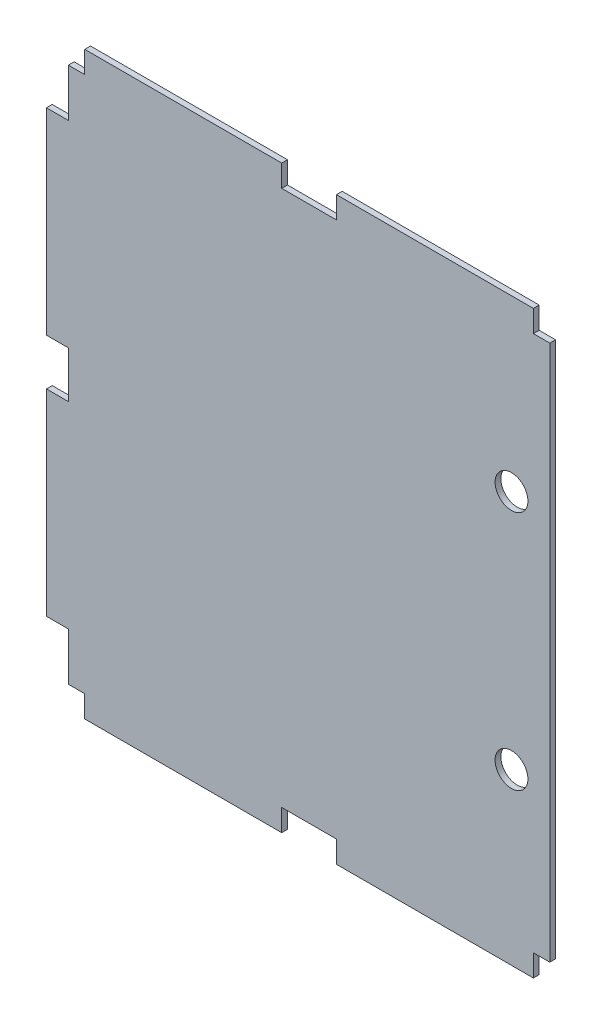
SolidWorks part; units mm, degrees
ref_plane "Front Plane" through (0, 0, 0) normal (0, 0, 1) x (1, 0, 0)
ref_plane "Top Plane" through (0, 0, 0) normal (0, 1, 0) x (1, 0, 0)
ref_plane "Right Plane" through (0, 0, 0) normal (1, 0, 0) x (0, 0, -1)
sketch "Sketch1" plane through (0, 0, 0) normal (0, 0, 1) x (1, 0, 0)
  line L0 (0, 0) -> (0, 155.575) construction
  line L1 (-139.7, -155.575) -> (139.7, -155.575)
  line L2 (-139.7, -155.575) -> (-139.7, 155.575)
  line L3 (-139.7, 155.575) -> (139.7, 155.575)
  line L4 (139.7, -155.575) -> (139.7, 155.575)
  line L5 (-139.7, -155.575) -> (139.7, 155.575) construction
  line L6 (-139.7, 155.575) -> (139.7, -155.575) construction
  line L7 (-130.175, 155.575) -> (-15.875, 155.575)
  line L8 (-130.175, 155.575) -> (-130.175, 168.275)
  line L9 (-130.175, 168.275) -> (-15.875, 168.275)
  line L10 (-15.875, 155.575) -> (-15.875, 168.275)
  line L11 (15.875, 155.575) -> (130.175, 155.575)
  line L12 (15.875, 155.575) -> (15.875, 168.275)
  line L13 (15.875, 168.275) -> (130.175, 168.275)
  line L14 (130.175, 155.575) -> (130.175, 168.275)
  line L15 (0, 155.575) -> (0, -155.575) construction
  line L16 (0, 0) -> (-139.7, 0) construction
  line L17 (-139.7, 0) -> (139.7, 0) construction
  line L18 (-15.875, -155.575) -> (-130.175, -155.575)
  line L19 (-15.875, -155.575) -> (-15.875, -168.275)
  line L20 (-15.875, -168.275) -> (-130.175, -168.275)
  line L21 (-130.175, -155.575) -> (-130.175, -168.275)
  line L22 (130.175, -155.575) -> (15.875, -155.575)
  line L23 (130.175, -155.575) -> (130.175, -168.275)
  line L24 (130.175, -168.275) -> (15.875, -168.275)
  line L25 (15.875, -155.575) -> (15.875, -168.275)
  line L26 (-139.7, 127.7938) -> (-152.4, 127.7938)
  line L27 (-139.7, 127.7938) -> (-139.7, 13.4938)
  line L28 (-139.7, 13.4938) -> (-152.4, 13.4938)
  line L29 (-152.4, 127.7938) -> (-152.4, 13.4938)
  line L30 (-139.7, -13.4938) -> (-152.4, -13.4938)
  line L31 (-139.7, -13.4938) -> (-139.7, -127.7937)
  line L32 (-139.7, -127.7937) -> (-152.4, -127.7938)
  line L33 (-152.4, -13.4938) -> (-152.4, -127.7938)
  point P0 (0, 0)
  point P34 (-152.4, -16.8592)
  point P35 (-146.05, -13.4938)
  dimension "D1" = 311.15
  dimension "D2" = 279.4
  dimension "D3" = 114.3
  dimension "D4" = 114.3
  dimension "D5" = 9.525
  dimension "D6" = 9.525
  dimension "D7" = 12.7
  dimension "D8" = 12.7
  dimension "D9" = 9.525
  dimension "D10" = 12.7
  dimension "D11" = 9.525
  dimension "D12" = 12.7
  dimension "D13" = 114.3
  dimension "D14" = 114.3
  dimension "D15" = 114.3
  dimension "D16" = 114.3
  dimension "D17" = 13.4937
  dimension "D18" = 13.4937
  dimension "D19" = 12.7
  dimension "D20" = 12.7
extrude "Boss-Extrude1" add sketch "Sketch1" along normal blind 3.3528 contours L1 L4 L3 L2 | L1 L21 L20 L19 | L1 L25 L24 L23 | L30 L33 L32 L2 | L26 L29 L28 L2 | L13 L14 L11 L12 | L9 L10 L7 L8
sketch "Sketch2" plane through (0, 0, 3.3528) normal (0, 0, 1) x (1, 0, 0)
  line L0 (139.7, 155.575) -> (139.7, 60.325) construction
  line L1 (139.7, -155.575) -> (139.7, 155.575) construction
  line L2 (15.875, 168.275) -> (130.175, 168.275) construction
  line L4 (139.7, 60.325) -> (139.7, 79.375)
  line L7 (0, 0) -> (139.7, 0) construction
  line L8 (139.7, 0) -> (-139.7, 0) construction
  line L9 (-139.7, -13.4938) -> (-139.7, 13.4938) construction
  circle A0 centre (117.475, 69.85) radius 9.525
  circle A1 centre (117.475, -69.85) radius 9.525
  dimension "D4" = 98.425
  dimension "D2" = 22.225
  dimension "D3" = 19.05
  dimension "D1" = 95.25
extrude "Cut-Extrude1" cut sketch "Sketch2" against normal blind 6.7056 contours A0 | A1
